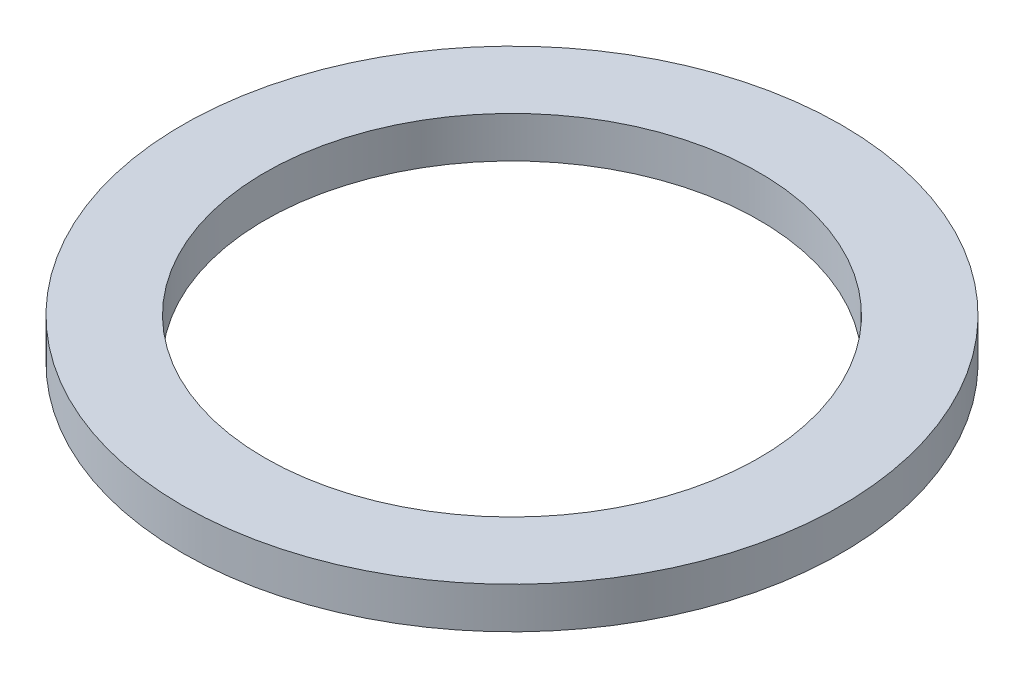
SolidWorks part; units mm, degrees
material "AISI 304"
ref_plane "Front" through (0, 0, 0) normal (0, 0, 1) x (1, 0, 0)
ref_plane "Top" through (0, 0, 0) normal (0, 1, 0) x (1, 0, 0)
ref_plane "Right" through (0, 0, 0) normal (1, 0, 0) x (0, 0, -1)
sketch "Sketch1" plane through (0, 0, 0) normal (0, 1, 0) x (1, 0, 0)
  circle A0 centre (0, 0) radius 6
  circle A1 centre (0, 0) radius 8
  dimension "D1" = 16
  dimension "D2" = 12
extrude "Boss-Extrude1" add sketch "Sketch1" along normal blind 1
